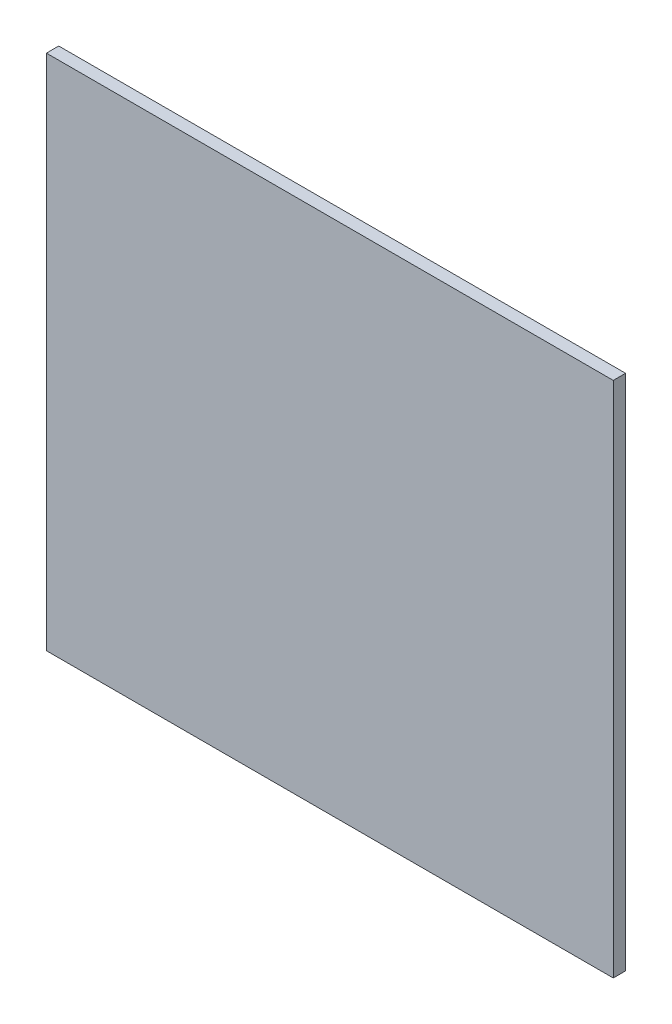
SolidWorks part; units mm, degrees
ref_plane "Plan de face" through (0, 0, 0) normal (0, 0, 1) x (1, 0, 0)
ref_plane "Plan de dessus" through (0, 0, 0) normal (0, 1, 0) x (1, 0, 0)
ref_plane "Plan de droite" through (0, 0, 0) normal (1, 0, 0) x (0, 0, -1)
sketch "Esquisse1" plane through (0, 0, 0) normal (0, 0, 1) x (1, 0, 0)
  line L1 (23, -21) -> (-23, -21)
  line L2 (23, -21) -> (23, 21)
  line L3 (23, 21) -> (-23, 21)
  line L4 (-23, -21) -> (-23, 21)
  line L5 (23, -21) -> (-23, 21) construction
  line L6 (23, 21) -> (-23, -21) construction
  point P0 (0, 0)
  dimension "D1" = 42
  dimension "D2" = 46
extrude "Boss.-Extru.1" add sketch "Esquisse1" along normal blind 1
